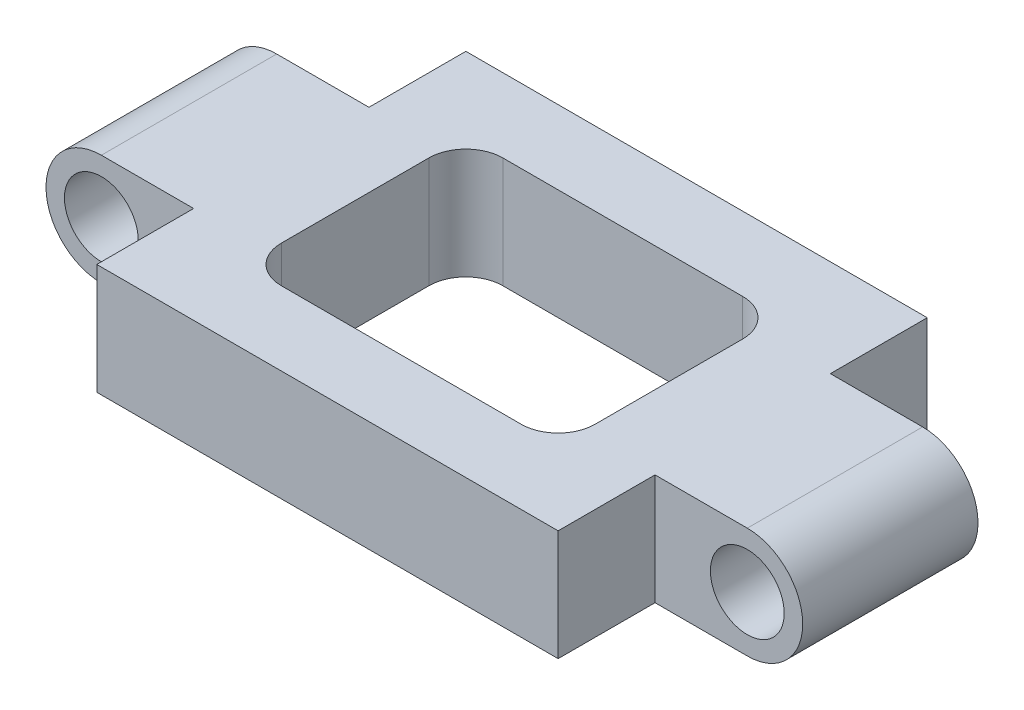
SolidWorks part; units mm, degrees
material "ABS"
ref_plane "Front Plane" through (0, 0, 0) normal (0, 0, 1) x (1, 0, 0)
ref_plane "Top Plane" through (0, 0, 0) normal (0, 1, 0) x (1, 0, 0)
ref_plane "Right Plane" through (0, 0, 0) normal (1, 0, 0) x (0, 0, -1)
sketch "Sketch1" plane through (0, 0, 0) normal (0, 0, 1) x (1, 0, 0)
  line L0 (17.5, 0) -> (-17.5, 0) construction
  line L1 (17.5, -3) -> (-17.5, -3)
  line L2 (17.5, 3) -> (-17.5, 3)
  arc A0 (17.5, -3) -> (17.5, 3) centre (17.5, 0) ccw
  arc A1 (-17.5, 3) -> (-17.5, -3) centre (-17.5, 0) ccw
  circle A2 centre (17.5, 0) radius 2
  circle A3 centre (-17.5, 0) radius 2
  point P2 (0, 0)
  dimension "D2" = 4
  dimension "D3" = 3
  dimension "40" = 35
extrude "Boss-Extrude1" add sketch "Sketch1" along normal mid plane 20
sketch "Sketch2" plane through (0, 3, 0) normal (0, 1, 0) x (1, 0, 0)
  line L1 (0, 10) -> (0, -10) construction
  line L2 (17.5, 10) -> (-17.5, 10) construction
  line L3 (17.5, -10) -> (-17.5, -10) construction
  line L4 (-12.5, -10) -> (-12.5, -4.75)
  line L6 (-17.5, 0) -> (17.5, 0) construction
  line L7 (-17.5, -10) -> (-17.5, 10) construction
  line L8 (17.5, -10) -> (17.5, 10) construction
  line L9 (-20.5, -4.75) -> (-12.5, -4.75)
  line L10 (-20.5, -10) -> (-20.5, -4.75)
  line L11 (-20.5, -10) -> (-12.5, -10)
  line L12 (-12.5, 4.75) -> (-12.5, 10)
  line L13 (20.5, -10) -> (20.5, 10) construction
  line L14 (20.5, 4.75) -> (12.5, 4.75)
  line L15 (20.5, 4.75) -> (20.5, 10)
  line L16 (20.5, 10) -> (12.5, 10)
  line L17 (12.5, 4.75) -> (12.5, 10)
  line L18 (20.5, -10) -> (12.5, -10)
  line L19 (20.5, -10) -> (20.5, -4.75)
  line L20 (-20.5, 10) -> (-12.5, 10)
  line L21 (20.5, -4.75) -> (12.5, -4.75)
  line L22 (12.5, -10) -> (12.5, -4.75)
  line L23 (-20.5, 4.75) -> (-20.5, 10)
  line L24 (-20.5, 4.75) -> (-12.5, 4.75)
  dimension "D3" = 8
  dimension "D4" = 9.5
extrude "Cut-Extrude3" cut sketch "Sketch2" against normal up to surface (6 mm away) up to face at (0, -3, 0)
sketch "Sketch3" plane through (0, 3, 0) normal (0, 1, 0) x (1, 0, 0)
  line L1 (8.5, 6) -> (-8.5, 6)
  line L2 (8.5, 6) -> (8.5, -6)
  line L3 (8.5, -6) -> (-8.5, -6)
  line L4 (-8.5, 6) -> (-8.5, -6)
  line L5 (8.5, 6) -> (-8.5, -6) construction
  line L6 (8.5, -6) -> (-8.5, 6) construction
  line L7 (-12.5, 4.75) -> (-12.5, 10) construction
  line L8 (12.5, 10) -> (-12.5, 10) construction
  line L9 (12.5, -10) -> (-12.5, -10) construction
  line L10 (12.5, 10) -> (12.5, 4.75) construction
  point P0 (0, 0)
  dimension "D1" = 4
  dimension "D2" = 4
  dimension "D3" = 4
  dimension "D4" = 4
extrude "Cut-Extrude4" cut sketch "Sketch3" against normal blind 10
fillet "Fillet1" radius 2 4 edges at (-8.5, 0, 6) (8.5, 0, 6) (8.5, 0, -6) (-8.5, 0, -6)
